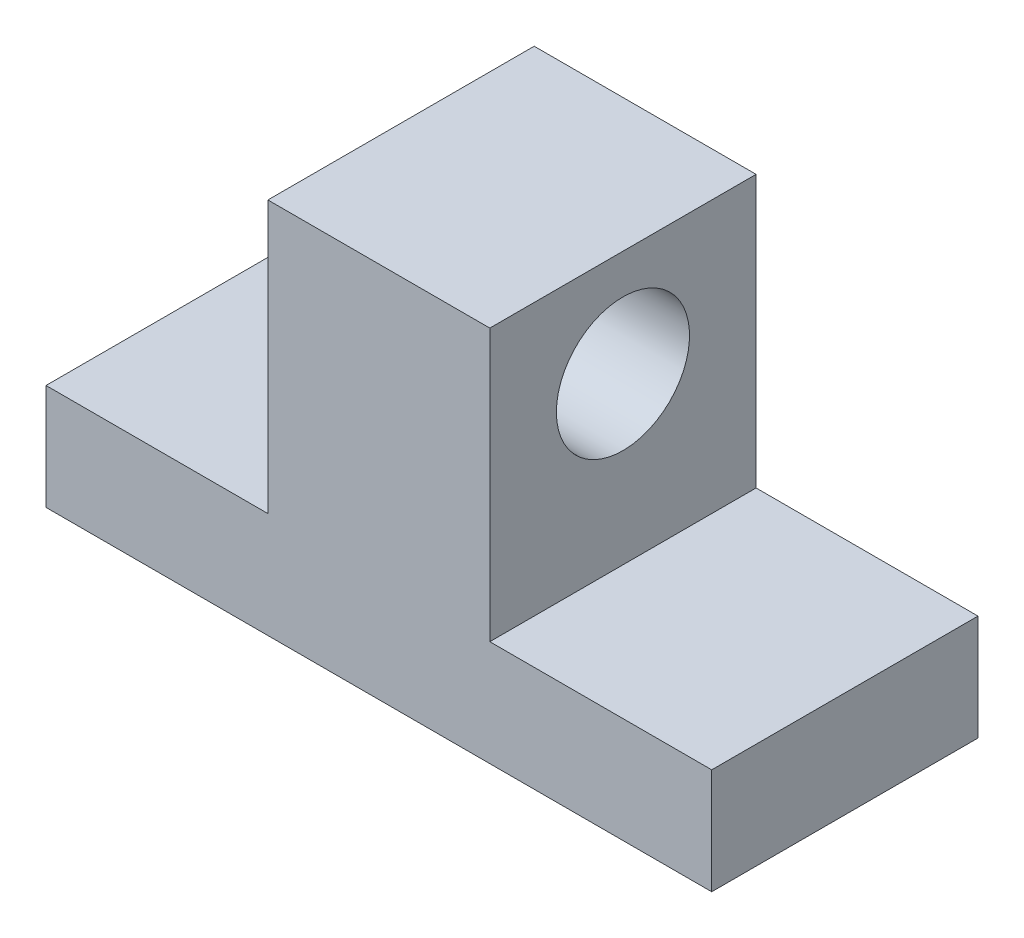
SolidWorks part; units mm, degrees
ref_plane "Спереди" through (0, 0, 0) normal (0, 0, 1) x (1, 0, 0)
ref_plane "Сверху" through (0, 0, 0) normal (0, 1, 0) x (1, 0, 0)
ref_plane "Справа" through (0, 0, 0) normal (1, 0, 0) x (0, 0, -1)
sketch "Эскиз2" plane through (0, 0, 0) normal (0, 0, 1) x (1, 0, 0)
  line L0 (0.8464, 0) -> (-29.1536, 0)
  line L1 (-14.1536, 0) -> (-14.1536, 18.4945) construction
  line L2 (-19.1536, 4.7601) -> (-19.1536, 17)
  line L3 (-24.1536, 24.0399) -> (-24.1536, 11.5951) construction
  line L4 (-29.1536, 4.7601) -> (-29.1536, 0)
  line L5 (-29.1536, 4.7601) -> (-19.1536, 4.7601)
  line L6 (-19.1536, 17) -> (-9.1536, 17)
  line L7 (0.8464, 4.7601) -> (-9.1536, 4.7601)
  line L8 (0.8464, 4.7601) -> (0.8464, 0)
  line L9 (-9.1536, 4.7601) -> (-9.1536, 17)
  point P11 (-14.1536, 17)
  dimension "D1" = 10
  dimension "D2" = 17
extrude "Вытянуть2" add sketch "Эскиз2" along normal blind 12
sketch "Эскиз4" plane through (-19.1536, 0, 0) normal (-1, 0, 0) x (0, 0, 1)
  circle A0 centre (6, 12.217) radius 3
extrude "Вытянуть4" cut sketch "Эскиз4" against normal through all
